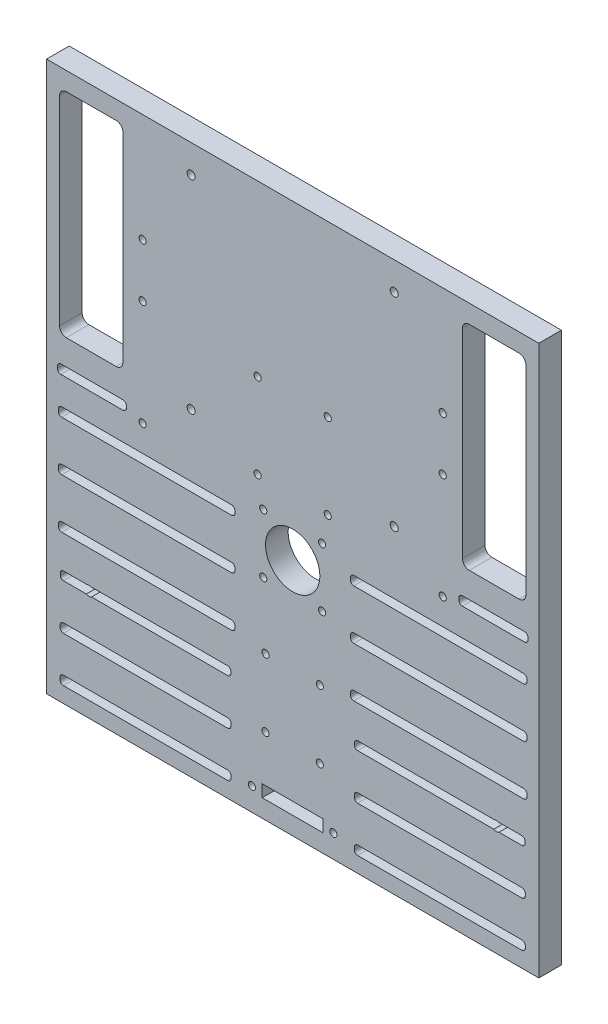
SolidWorks part; units mm, degrees
ref_plane "Front Plane" through (0, 0, 0) normal (0, 0, 1) x (1, 0, 0)
ref_plane "Top Plane" through (0, 0, 0) normal (0, 1, 0) x (1, 0, 0)
ref_plane "Right Plane" through (0, 0, 0) normal (1, 0, 0) x (0, 0, -1)
sketch "Model" plane through (0, 0, 0) normal (0, 0, 1) x (1, 0, 0)
  line L0 (-154.1053, -41.3499) -> (-93.977, -41.3499)
  line L1 (-92.602, -39.9749) -> (-92.602, -38.9749)
  line L2 (-93.977, -37.5999) -> (-154.4698, -37.5999)
  line L3 (-156.0625, -37.5999) -> (-166.5277, -37.5999)
  line L4 (-167.9027, -38.9749) -> (-167.9027, -39.9749)
  line L5 (-166.5277, -41.3499) -> (-156.4271, -41.3499)
  line L6 (37.4953, -59.9749) -> (37.4953, -58.9749)
  line L7 (-36.5554, -61.4749) -> (35.9953, -61.4749)
  line L8 (-38.0554, -58.9749) -> (-38.0554, -59.9749)
  line L9 (35.9953, -57.4749) -> (-36.5554, -57.4749)
  line L10 (-90.7703, -21.6638) -> (-90.7703, -20.6638)
  line L11 (-167.2842, -23.1638) -> (-92.2703, -23.1638)
  line L12 (-168.7842, -20.6638) -> (-168.7842, -21.6638)
  line L13 (-92.2703, -19.1638) -> (-167.2842, -19.1638)
  line L14 (-90.7703, 22.3362) -> (-90.7703, 23.3362)
  line L15 (-167.2842, 20.8362) -> (-92.2703, 20.8362)
  line L16 (-168.7842, 23.3362) -> (-168.7842, 22.3362)
  line L17 (-92.2703, 24.8362) -> (-167.2842, 24.8362)
  line L18 (-90.7703, 0.3362) -> (-90.7703, 1.3362)
  line L19 (-167.2842, -1.1638) -> (-92.2703, -1.1638)
  line L20 (-168.7842, 1.3362) -> (-168.7842, 0.3362)
  line L21 (-92.2703, 2.8362) -> (-167.2842, 2.8362)
  line L22 (37.4953, -79.9749) -> (37.4953, -78.9749)
  line L23 (-36.5554, -81.4749) -> (35.9953, -81.4749)
  line L24 (-38.0554, -78.9749) -> (-38.0554, -79.9749)
  line L25 (35.9953, -77.4749) -> (-36.5554, -77.4749)
  line L26 (-92.477, -59.9749) -> (-92.477, -58.9749)
  line L27 (-166.5277, -61.4749) -> (-93.977, -61.4749)
  line L28 (-168.0277, -58.9749) -> (-168.0277, -59.9749)
  line L29 (-93.977, -57.4749) -> (-166.5277, -57.4749)
  line L30 (-92.477, -79.9749) -> (-92.477, -78.9749)
  line L31 (-166.5277, -81.4749) -> (-93.977, -81.4749)
  line L32 (-168.0277, -78.9749) -> (-168.0277, -79.9749)
  line L33 (-93.977, -77.4749) -> (-166.5277, -77.4749)
  line L34 (9.6846, 37.0358) -> (37.1634, 37.0358)
  line L35 (8.1846, 39.5358) -> (8.1846, 38.5358)
  line L36 (37.1634, 41.0358) -> (9.6846, 41.0358)
  line L37 (38.6634, 38.5358) -> (38.6634, 39.5358)
  line L38 (-138.717, 38.5358) -> (-138.717, 39.5358)
  line L39 (-167.6958, 37.0358) -> (-140.217, 37.0358)
  line L40 (-169.1958, 39.5358) -> (-169.1958, 38.5358)
  line L41 (-140.217, 41.0358) -> (-167.6958, 41.0358)
  line L42 (38.2518, 22.3362) -> (38.2518, 23.3362)
  line L43 (-38.2621, 20.8362) -> (36.7518, 20.8362)
  line L44 (-39.7621, 23.3362) -> (-39.7621, 22.3362)
  line L45 (36.7518, 24.8362) -> (-38.2621, 24.8362)
  line L46 (-38.2621, -1.1638) -> (36.7518, -1.1638)
  line L47 (-39.7621, 1.3362) -> (-39.7621, 0.3362)
  line L48 (36.7518, 2.8362) -> (-38.2621, 2.8362)
  line L49 (38.2518, 0.3362) -> (38.2518, 1.3362)
  line L50 (-38.2621, -23.1638) -> (36.7518, -23.1638)
  line L51 (-39.7621, -20.6638) -> (-39.7621, -21.6638)
  line L52 (36.7518, -19.1638) -> (-38.2621, -19.1638)
  line L53 (38.2518, -21.6638) -> (38.2518, -20.6638)
  line L54 (-173.9912, -88.3391) -> (43.4588, -88.3391)
  line L55 (43.4588, -88.3391) -> (43.4588, 154.5091)
  line L56 (43.4588, 154.5091) -> (-173.9912, 154.5091)
  line L57 (-173.9912, 154.5091) -> (-173.9912, -88.3391)
  line L64 (9.7338, 143.3841) -> (9.7338, 55.2603)
  line L65 (34.7338, 146.3841) -> (12.7338, 146.3841)
  line L66 (37.7338, 55.2603) -> (37.7338, 143.3841)
  line L67 (12.7338, 52.2603) -> (34.7338, 52.2603)
  line L68 (-165.2662, 52.2603) -> (-143.2662, 52.2603)
  line L69 (-168.2662, 143.3841) -> (-168.2662, 55.2603)
  line L70 (-143.2662, 146.3841) -> (-165.2662, 146.3841)
  line L71 (-140.2662, 55.2603) -> (-140.2662, 143.3841)
  line L72 (-51.8026, -80.4578) -> (-51.8026, -75.1009)
  line L73 (-51.8026, -80.4578) -> (-78.7298, -80.4578)
  line L74 (-78.7298, -80.4578) -> (-78.7298, -75.1009)
  line L75 (-78.7298, -75.1009) -> (-51.8026, -75.1009)
  line L76 (25.8947, -41.3499) -> (35.9953, -41.3499)
  line L77 (37.3703, -39.9749) -> (37.3703, -38.9749)
  line L78 (35.9953, -37.5999) -> (25.5302, -37.5999)
  line L79 (23.9375, -37.5999) -> (-36.5554, -37.5999)
  line L80 (-37.9304, -38.9749) -> (-37.9304, -39.9749)
  line L81 (-36.5554, -41.3499) -> (23.5729, -41.3499)
  arc A0 (-156.4271, -41.3499) -> (-154.1053, -41.3499) centre (-155.2662, -39.5701) ccw
  arc A1 (-93.977, -41.3499) -> (-92.602, -39.9749) centre (-93.977, -39.9749) ccw
  arc A2 (-92.602, -38.9749) -> (-93.977, -37.5999) centre (-93.977, -38.9749) ccw
  arc A3 (-154.4698, -37.5999) -> (-156.0625, -37.5999) centre (-155.2662, -39.5701) ccw
  arc A4 (-166.5277, -37.5999) -> (-167.9027, -38.9749) centre (-166.5277, -38.9749) ccw
  arc A5 (-167.9027, -39.9749) -> (-166.5277, -41.3499) centre (-166.5277, -39.9749) ccw
  arc A6 (37.4953, -58.9749) -> (35.9953, -57.4749) centre (35.9953, -58.9749) ccw
  arc A7 (35.9953, -61.4749) -> (37.4953, -59.9749) centre (35.9953, -59.9749) ccw
  arc A8 (-38.0554, -59.9749) -> (-36.5554, -61.4749) centre (-36.5554, -59.9749) ccw
  arc A9 (-36.5554, -57.4749) -> (-38.0554, -58.9749) centre (-36.5554, -58.9749) ccw
  arc A10 (-90.7703, -20.6638) -> (-92.2703, -19.1638) centre (-92.2703, -20.6638) ccw
  arc A11 (-92.2703, -23.1638) -> (-90.7703, -21.6638) centre (-92.2703, -21.6638) ccw
  arc A12 (-168.7842, -21.6638) -> (-167.2842, -23.1638) centre (-167.2842, -21.6638) ccw
  arc A13 (-167.2842, -19.1638) -> (-168.7842, -20.6638) centre (-167.2842, -20.6638) ccw
  arc A14 (-90.7703, 23.3362) -> (-92.2703, 24.8362) centre (-92.2703, 23.3362) ccw
  arc A15 (-92.2703, 20.8362) -> (-90.7703, 22.3362) centre (-92.2703, 22.3362) ccw
  arc A16 (-168.7842, 22.3362) -> (-167.2842, 20.8362) centre (-167.2842, 22.3362) ccw
  arc A17 (-167.2842, 24.8362) -> (-168.7842, 23.3362) centre (-167.2842, 23.3362) ccw
  arc A18 (-90.7703, 1.3362) -> (-92.2703, 2.8362) centre (-92.2703, 1.3362) ccw
  arc A19 (-92.2703, -1.1638) -> (-90.7703, 0.3362) centre (-92.2703, 0.3362) ccw
  arc A20 (-168.7842, 0.3362) -> (-167.2842, -1.1638) centre (-167.2842, 0.3362) ccw
  arc A21 (-167.2842, 2.8362) -> (-168.7842, 1.3362) centre (-167.2842, 1.3362) ccw
  arc A22 (37.4953, -78.9749) -> (35.9953, -77.4749) centre (35.9953, -78.9749) ccw
  arc A23 (35.9953, -81.4749) -> (37.4953, -79.9749) centre (35.9953, -79.9749) ccw
  arc A24 (-38.0554, -79.9749) -> (-36.5554, -81.4749) centre (-36.5554, -79.9749) ccw
  arc A25 (-36.5554, -77.4749) -> (-38.0554, -78.9749) centre (-36.5554, -78.9749) ccw
  arc A26 (-92.477, -58.9749) -> (-93.977, -57.4749) centre (-93.977, -58.9749) ccw
  arc A27 (-93.977, -61.4749) -> (-92.477, -59.9749) centre (-93.977, -59.9749) ccw
  arc A28 (-168.0277, -59.9749) -> (-166.5277, -61.4749) centre (-166.5277, -59.9749) ccw
  arc A29 (-166.5277, -57.4749) -> (-168.0277, -58.9749) centre (-166.5277, -58.9749) ccw
  arc A30 (-92.477, -78.9749) -> (-93.977, -77.4749) centre (-93.977, -78.9749) ccw
  arc A31 (-93.977, -81.4749) -> (-92.477, -79.9749) centre (-93.977, -79.9749) ccw
  arc A32 (-168.0277, -79.9749) -> (-166.5277, -81.4749) centre (-166.5277, -79.9749) ccw
  arc A33 (-166.5277, -77.4749) -> (-168.0277, -78.9749) centre (-166.5277, -78.9749) ccw
  arc A34 (37.1634, 37.0358) -> (38.6634, 38.5358) centre (37.1634, 38.5358) ccw
  arc A35 (8.1846, 38.5358) -> (9.6846, 37.0358) centre (9.6846, 38.5358) ccw
  arc A36 (9.6846, 41.0358) -> (8.1846, 39.5358) centre (9.6846, 39.5358) ccw
  arc A37 (38.6634, 39.5358) -> (37.1634, 41.0358) centre (37.1634, 39.5358) ccw
  arc A38 (-138.717, 39.5358) -> (-140.217, 41.0358) centre (-140.217, 39.5358) ccw
  arc A39 (-140.217, 37.0358) -> (-138.717, 38.5358) centre (-140.217, 38.5358) ccw
  arc A40 (-169.1958, 38.5358) -> (-167.6958, 37.0358) centre (-167.6958, 38.5358) ccw
  arc A41 (-167.6958, 41.0358) -> (-169.1958, 39.5358) centre (-167.6958, 39.5358) ccw
  arc A42 (38.2518, 23.3362) -> (36.7518, 24.8362) centre (36.7518, 23.3362) ccw
  arc A43 (36.7518, 20.8362) -> (38.2518, 22.3362) centre (36.7518, 22.3362) ccw
  arc A44 (-39.7621, 22.3362) -> (-38.2621, 20.8362) centre (-38.2621, 22.3362) ccw
  arc A45 (-38.2621, 24.8362) -> (-39.7621, 23.3362) centre (-38.2621, 23.3362) ccw
  arc A46 (36.7518, -1.1638) -> (38.2518, 0.3362) centre (36.7518, 0.3362) ccw
  arc A47 (-39.7621, 0.3362) -> (-38.2621, -1.1638) centre (-38.2621, 0.3362) ccw
  arc A48 (-38.2621, 2.8362) -> (-39.7621, 1.3362) centre (-38.2621, 1.3362) ccw
  arc A49 (38.2518, 1.3362) -> (36.7518, 2.8362) centre (36.7518, 1.3362) ccw
  arc A50 (36.7518, -23.1638) -> (38.2518, -21.6638) centre (36.7518, -21.6638) ccw
  arc A51 (-39.7621, -21.6638) -> (-38.2621, -23.1638) centre (-38.2621, -21.6638) ccw
  arc A52 (-38.2621, -19.1638) -> (-39.7621, -20.6638) centre (-38.2621, -20.6638) ccw
  arc A53 (38.2518, -20.6638) -> (36.7518, -19.1638) centre (36.7518, -20.6638) ccw
  arc A60 (35.9953, -41.3499) -> (37.3703, -39.9749) centre (35.9953, -39.9749) ccw
  arc A61 (37.3703, -38.9749) -> (35.9953, -37.5999) centre (35.9953, -38.9749) ccw
  arc A62 (25.5302, -37.5999) -> (23.9375, -37.5999) centre (24.7338, -39.5701) ccw
  arc A63 (-36.5554, -37.5999) -> (-37.9304, -38.9749) centre (-36.5554, -38.9749) ccw
  arc A64 (-37.9304, -39.9749) -> (-36.5554, -41.3499) centre (-36.5554, -39.9749) ccw
  arc A65 (23.5729, -41.3499) -> (25.8947, -41.3499) centre (24.7338, -39.5701) ccw
  arc A84 (12.7338, 146.3841) -> (9.7338, 143.3841) centre (12.7338, 143.3841) ccw
  arc A85 (37.7338, 143.3841) -> (34.7338, 146.3841) centre (34.7338, 143.3841) ccw
  arc A86 (34.7338, 52.2603) -> (37.7338, 55.2603) centre (34.7338, 55.2603) ccw
  arc A87 (9.7338, 55.2603) -> (12.7338, 52.2603) centre (12.7338, 55.2603) ccw
  arc A88 (-168.2662, 55.2603) -> (-165.2662, 52.2603) centre (-165.2662, 55.2603) ccw
  arc A89 (-165.2662, 146.3841) -> (-168.2662, 143.3841) centre (-165.2662, 143.3841) ccw
  arc A90 (-140.2662, 143.3841) -> (-143.2662, 146.3841) centre (-143.2662, 143.3841) ccw
  arc A91 (-143.2662, 52.2603) -> (-140.2662, 55.2603) centre (-143.2662, 55.2603) ccw
  circle A92 centre (-65.2662, 17.0799) radius 12
  circle A93 centre (-83.2662, -78.2141) radius 1.575
  circle A94 centre (-47.2662, -78.2141) radius 1.575
  circle A95 centre (-53.2662, -54.6349) radius 1.575
  circle A96 centre (-77.2662, -54.6349) radius 1.575
  circle A97 centre (-77.2662, -24.6349) radius 1.575
  circle A98 centre (-53.2662, -24.6349) radius 1.575
  circle A99 centre (-52.2662, 4.0799) radius 1.575
  circle A100 centre (-78.2662, 4.0799) radius 1.575
  circle A101 centre (-78.2662, 30.0799) radius 1.575
  circle A102 centre (-52.2662, 30.0799) radius 1.575
  circle A103 centre (-49.7803, 42.2194) radius 1.575
  circle A104 centre (-80.7521, 42.2194) radius 1.575
  circle A105 centre (-131.5463, 36.3977) radius 1.575
  circle A106 centre (1.0139, 36.3977) radius 1.575
  circle A107 centre (-110.1162, 52.4299) radius 1.775
  circle A108 centre (-20.4162, 52.4299) radius 1.775
  circle A109 centre (-49.7803, 79.6224) radius 1.575
  circle A110 centre (-80.7521, 79.6224) radius 1.575
  circle A111 centre (-131.5463, 83.1098) radius 1.575
  circle A112 centre (1.0139, 83.1098) radius 1.575
  circle A113 centre (1.0139, 106.6172) radius 1.575
  circle A114 centre (-20.4162, 142.1299) radius 1.775
  circle A115 centre (-110.1162, 142.1299) radius 1.775
  circle A116 centre (-131.5463, 106.6172) radius 1.575
  point P260 (0, 0)
extrude "Boss-Extrude1" add sketch "Model" along normal blind 10
